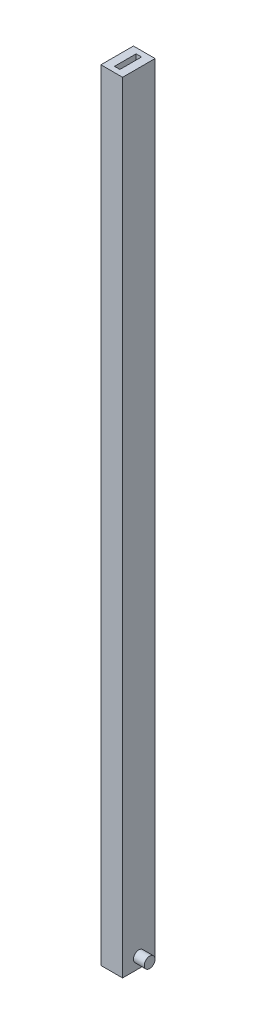
SolidWorks part; units mm, degrees
ref_plane "Front Plane" through (0, 0, 0) normal (0, 0, 1) x (1, 0, 0)
ref_plane "Top Plane" through (0, 0, 0) normal (0, 1, 0) x (1, 0, 0)
ref_plane "Right Plane" through (0, 0, 0) normal (1, 0, 0) x (0, 0, -1)
sketch "Sketch1" plane through (0, 0, 0) normal (0, 1, 0) x (1, 0, 0)
  line L1 (-6.35, -9.525) -> (6.35, -9.525)
  line L2 (-6.35, -9.525) -> (-6.35, 9.525)
  line L3 (-6.35, 9.525) -> (6.35, 9.525)
  line L4 (6.35, -9.525) -> (6.35, 9.525)
  line L5 (-6.35, -9.525) -> (6.35, 9.525) construction
  line L6 (-6.35, 9.525) -> (6.35, -9.525) construction
  line L7 (-1.5875, -6.35) -> (1.5875, -6.35)
  line L8 (-1.5875, -6.35) -> (-1.5875, 6.35)
  line L9 (-1.5875, 6.35) -> (1.5875, 6.35)
  line L10 (1.5875, -6.35) -> (1.5875, 6.35)
  line L11 (-1.5875, -6.35) -> (1.5875, 6.35) construction
  line L12 (-1.5875, 6.35) -> (1.5875, -6.35) construction
  point P0 (0, 0)
  point P6 (0, 0)
extrude "Boss-Extrude1" add sketch "Sketch1" along normal blind 457.2
sketch "Sketch2" plane through (-1.5875, 0, 0) normal (1, 0, 0) x (0, 0, -1)
  line L0 (6.35, 457.2) -> (6.35, 0) construction
  line L1 (6.35, 457.2) -> (-6.35, 457.2) construction
  circle A0 centre (0, 450.85) radius 3.175
  point P6 (-7.2347, 460.7913)
  dimension "D1" = 6.35
  dimension "D2" = 6.35
extrude "Boss-Extrude2" add sketch "Sketch2" along normal up to next
sketch "Sketch3" plane through (6.35, 0, 0) normal (1, 0, 0) x (0, 0, -1)
  line L0 (-9.525, 457.2) -> (-9.525, 0) construction
  line L1 (-9.525, 0) -> (9.525, 0) construction
  circle A0 centre (0, 6.35) radius 3.175
  dimension "D1" = 9.525
  dimension "D2" = 6.35
extrude "Boss-Extrude3" add sketch "Sketch3" along normal blind 6.35
sketch "Sketch4" plane through (-6.35, 0, 0) normal (-1, 0, 0) x (0, 0, 1)
  line L0 (-9.525, 0) -> (9.525, 0) construction
  line L1 (-9.525, 457.2) -> (-9.525, 0) construction
  circle A0 centre (0, 6.35) radius 3.175
  dimension "D1" = 6.35
  dimension "D2" = 9.525
extrude "Boss-Extrude4" add sketch "Sketch4" along normal blind 6.35
